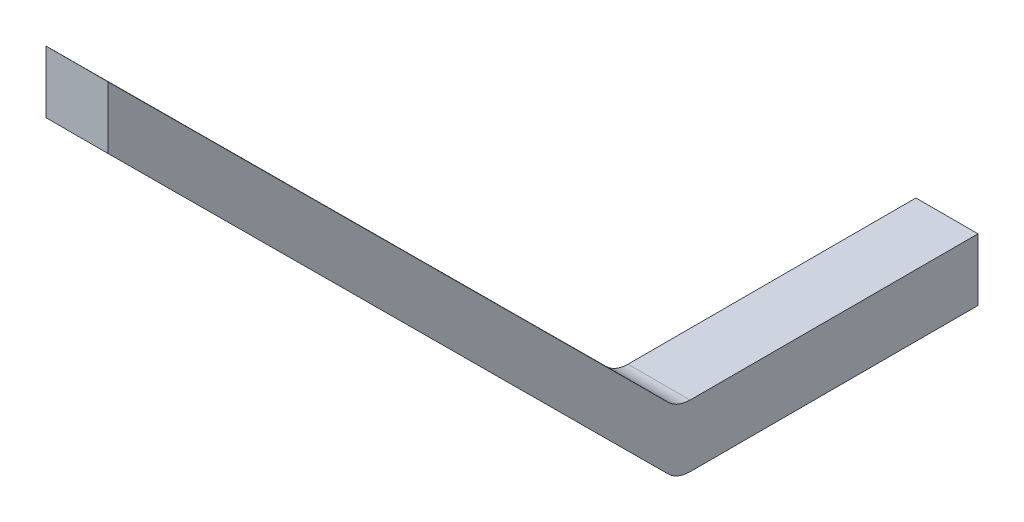
SolidWorks part; units mm, degrees
ref_plane "Front Plane" through (0, 0, 0) normal (0, 0, 1) x (1, 0, 0)
ref_plane "Top Plane" through (0, 0, 0) normal (0, 1, 0) x (1, 0, 0)
ref_plane "Right Plane" through (0, 0, 0) normal (1, 0, 0) x (0, 0, -1)
sketch "Sketch1" plane through (0, 0, 0) normal (1, 0, 0) x (0, 0, -1)
  line L0 (0, 0) -> (-29.0674, 0)
  line L1 (-29.0674, 0) -> (-84.0674, 0) construction
  line L2 (-84.0674, 0) -> (-84.0674, 60.75) construction
  line L3 (0, 0) -> (0, 6)
  line L4 (0, 6) -> (-29.0674, 6)
  line L5 (-84.0674, 60.75) -> (-84.0674, 54.75)
  line L6 (-84.0674, 54.75) -> (-29.0674, 0)
  line L7 (-29.0674, 6) -> (-84.0674, 60.75)
  dimension "D1" = 55
  dimension "D2" = 60.75
  dimension "D3" = 6
extrude "Boss-Extrude1" add sketch "Sketch1" along normal blind 6
fillet "Fillet1" radius 3 2 edges at (3, 6, 29.0674) (3, 0, 29.0674)
